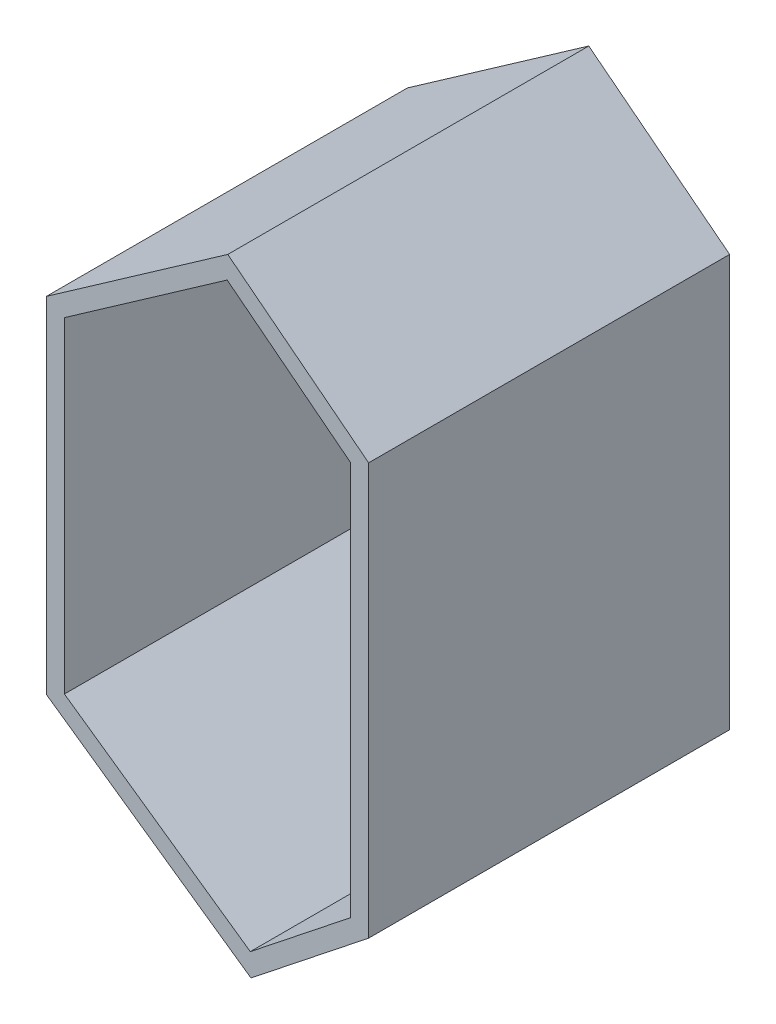
SolidWorks part; units mm, degrees
ref_plane "Спереди" through (0, 0, 0) normal (0, 0, 1) x (1, 0, 0)
ref_plane "Сверху" through (0, 0, 0) normal (0, 1, 0) x (1, 0, 0)
ref_plane "Справа" through (0, 0, 0) normal (1, 0, 0) x (0, 0, -1)
sketch "Sketch1" plane through (0, 0, 0) normal (0, 0, 1) x (1, 0, 0)
  line L0 (23.0022, -29.3716) -> (18.3201, -25.7135)
  line L1 (18.3201, -25.7135) -> (17.8061, -26.0734)
  line L2 (23.0022, -29.3716) -> (23.0022, -43.0552)
  line L3 (23.0022, -43.0552) -> (19.0913, -46.1568)
  line L4 (22.7398, -43.2633) -> (19.0913, -46.1568) construction
  line L5 (23.0022, -29.3716) -> (18.5624, -25.9028) construction
  line L7 (18.1503, -26.5649) -> (12.8903, -30.2479)
  line L8 (12.8903, -30.2479) -> (12.8903, -41.0824)
  line L9 (12.8903, -41.0824) -> (19.0689, -45.4087)
  line L10 (22.4022, -42.7653) -> (19.0689, -45.4087)
  line L11 (22.4022, -29.6642) -> (22.4022, -42.7653)
  line L12 (22.4022, -29.6642) -> (18.3005, -26.4596)
  line L13 (18.3005, -26.4596) -> (18.1503, -26.5649)
  line L25 (25.9585, -43.2633) -> (49.5222, -43.2633)
  line L26 (49.5222, -43.2633) -> (53.1707, -46.1568)
  line L27 (53.1707, -46.1568) -> (56.3894, -46.1568)
  line L28 (56.3894, -46.1568) -> (63.1903, -41.3947)
  line L29 (63.1903, -41.3947) -> (63.1903, -29.9356)
  line L30 (63.1903, -29.9356) -> (57.6745, -26.0734)
  line L31 (57.6745, -26.0734) -> (56.3894, -23.5057)
  line L32 (56.3894, -23.5057) -> (56.5858, 10.3664)
  line L33 (56.5858, 10.3664) -> (63.1903, 15.8272)
  line L34 (63.1903, 15.8272) -> (63.1903, 35.4209)
  line L35 (63.1903, 35.4209) -> (60.4666, 47.8767)
  line L36 (60.4666, 47.8767) -> (51.7869, 62.8585)
  line L37 (51.7869, 62.8585) -> (37.7403, 62.94)
  line L38 (37.7403, 62.94) -> (23.6938, 62.8585)
  line L39 (23.6938, 62.8585) -> (15.0141, 47.8767)
  line L40 (15.0141, 47.8767) -> (12.2903, 35.4209)
  line L41 (12.2903, 35.4209) -> (12.2903, 15.8272)
  line L42 (12.2903, 15.8272) -> (18.8948, 10.3664)
  line L43 (18.8948, 10.3664) -> (19.0913, -23.5057)
  line L44 (19.0913, -23.5057) -> (17.8061, -26.0734)
  line L45 (17.8061, -26.0734) -> (12.2903, -29.9356)
  line L46 (12.2903, -29.9356) -> (12.2903, -41.3947)
  line L47 (12.2903, -41.3947) -> (19.0913, -46.1568)
  line L48 (19.0913, -46.1568) -> (22.31, -46.1568)
  line L49 (22.31, -46.1568) -> (25.9585, -43.2633)
  line L70 (17.8061, -26.0734) -> (12.2903, -29.9356)
  line L71 (12.2903, -29.9356) -> (12.2903, -41.3947)
  line L72 (12.2903, -41.3947) -> (19.0913, -46.1568)
  dimension "D1" = 0
  dimension "D2" = 0.6
extrude "Boss-Extrude1" add sketch "Sketch1" along normal blind 12
